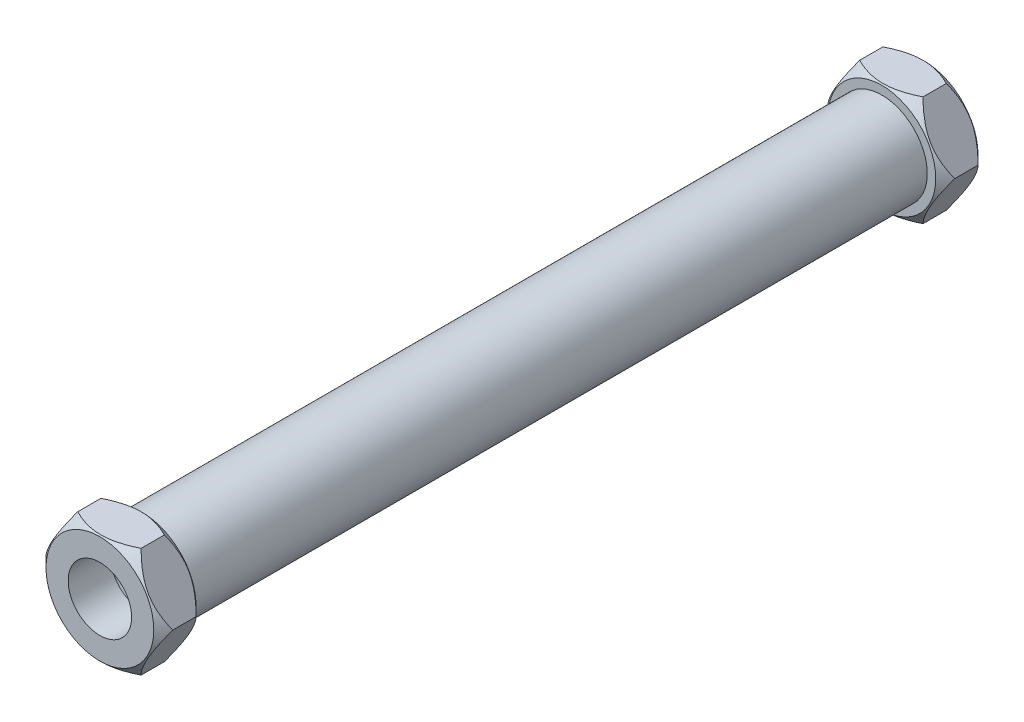
SolidWorks part; units mm, degrees
ref_plane "Front Plane" through (0, 0, 0) normal (0, 0, 1) x (1, 0, 0)
ref_plane "Top Plane" through (0, 0, 0) normal (0, 1, 0) x (1, 0, 0)
ref_plane "Right Plane" through (0, 0, 0) normal (1, 0, 0) x (0, 0, -1)
sketch3d "3DSketch1"
  line L0 (0, 0, 0) -> (0, 0, -140)
  point P0 (0, 0, 0)
  dimension "D1" = 140
other "Circular hollow section (c250) as 17.2X2.3 CHS C250(1)"
ref_plane "Plane1" through (0, 0, 0) normal (0, 0, -1) x (1, 0, 0)
sketch "Sketch1" plane through (0, 0, 0) normal (0, 0, -1) x (1, 0, 0)
  circle A0 centre (0, 0) radius 6.3
  circle A1 centre (0, 0) radius 8.6
  point P4 (0, 0)
  dimension "Out_dia" = 17.2
  dimension "Thickness" = 2.3
ref_plane "Plane2" through (0, 0, -70) normal (0, 0, 1) x (1, 0, 0)
sketch "Sketch2" plane through (0, 0, 0) normal (0, 0, 1) x (1, 0, 0)
  circle A0 centre (0, 0) radius 12
  dimension "D1" = 24
extrude "Boss-Extrude1" add sketch "Sketch2" along normal blind 8 separate body
chamfer "Chamfer1" distance 1.8 angle 45 2 edges at (12, 0, 0) (12, 0, 8)
sketch "Sketch3" plane through (0, 0, 8) normal (0, 0, 1) x (1, 0, 0)
  line L0 (-7.1547, 12.3923) -> (-14.3094, 0)
  line L1 (12, 0) -> (6, 10.3923)
  line L2 (6, 10.3923) -> (-6, 10.3923)
  line L3 (-6, 10.3923) -> (-12, 0)
  line L4 (-12, 0) -> (-6, -10.3923)
  line L5 (-6, -10.3923) -> (6, -10.3923)
  line L6 (6, -10.3923) -> (12, 0)
  line L7 (-14.3094, 0) -> (-7.1547, -12.3923)
  line L8 (-7.1547, -12.3923) -> (7.1547, -12.3923)
  line L9 (7.1547, -12.3923) -> (14.3094, 0)
  line L10 (14.3094, 0) -> (7.1547, 12.3923)
  line L11 (7.1547, 12.3923) -> (-7.1547, 12.3923)
  circle A0 centre (0, 0) radius 10.3923 construction
  circle A1 centre (0, 0) radius 6
  dimension "D2" = 12
  dimension "D1" = 2
extrude "Cut-Extrude1" cut sketch "Sketch3" against normal blind 16 contours L10 L11 L0 L7 L8 L9 L6 L5 L4 L3 L2 L1 | A1
mirror "Mirror1" about plane through (0, 0, -70) normal (0, 0, 1) of bodies 103
